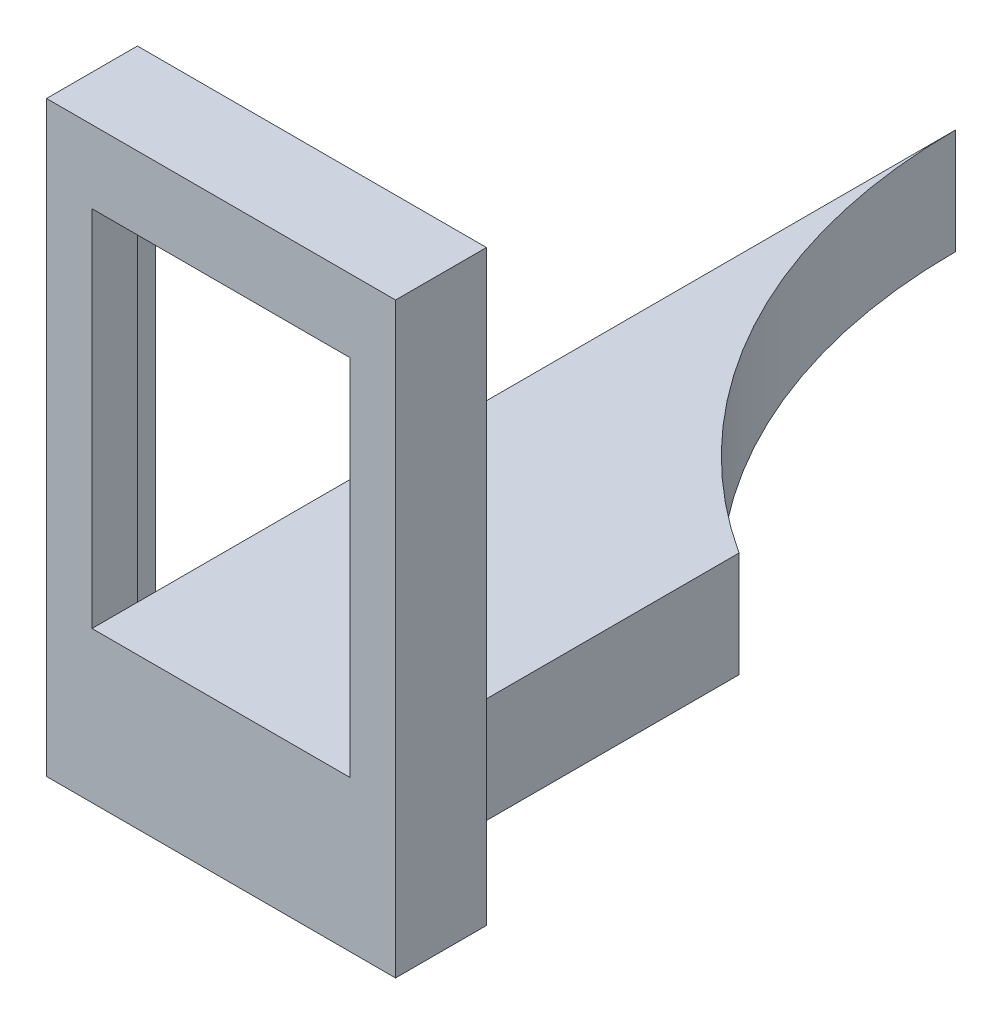
SolidWorks part; units mm, degrees
ref_plane "정면" through (0, 0, 0) normal (0, 0, 1) x (1, 0, 0)
ref_plane "윗면" through (0, 0, 0) normal (0, 1, 0) x (1, 0, 0)
ref_plane "우측면" through (0, 0, 0) normal (1, 0, 0) x (0, 0, -1)
sketch "스케치8" plane through (0, 0, 0) normal (0, 0, 1) x (1, 0, 0)
  line L0 (0, 60.6) -> (0, 0)
  line L1 (0, 0) -> (34.4, 0)
  line L2 (34.4, 0) -> (34.4, 60.6)
  line L3 (34.4, 60.6) -> (0, 60.6)
  line L4 (3, 54.6) -> (3, 3)
  line L5 (3, 3) -> (31.4, 3)
  line L6 (31.4, 3) -> (31.4, 54.6)
  line L7 (31.4, 54.6) -> (3, 54.6)
  point P8 (0, 0)
  point P9 (0, 0)
  dimension "D1" = 6
  dimension "D2" = 3
  dimension "D3" = 3
  dimension "D4" = 3
  dimension "D5" = 60.6
  dimension "D6" = 34.4
extrude "보스-돌출4" add sketch "스케치8" against normal blind 5
sketch "스케치9" plane through (0, 0, 0) normal (0, 0, 1) x (1, 0, 0)
  line L0 (31.4, 3) -> (31.4, 54.6) construction
  line L1 (3, 3) -> (31.4, 3)
  line L2 (3, 3) -> (3, 14.6)
  line L3 (3, 14.6) -> (31.4, 14.6)
  line L4 (31.4, 3) -> (31.4, 14.6)
  line L5 (31.4, 54.6) -> (3, 54.6) construction
  dimension "D1" = 40
extrude "보스-돌출5" add sketch "스케치9" against normal blind 95
sketch "스케치10" plane through (0, 14.6, 0) normal (0, 1, 0) x (1, 0, 0)
  circle A0 centre (65.2, 95) radius 62.2
  point P3 (0, 0)
  dimension "D1" = 124.4
extrude "컷-돌출3" cut sketch "스케치10" against normal blind 100
ref_plane "평면1" through (31.4, 14.6, -42.7851) normal (0, 0, 1) x (1, 0, 0)
sketch "스케치13" plane through (0, 0, 0) normal (0, 0, 1) x (1, 0, 0)
  line L0 (0, 60.6) -> (0, 0) construction
  line L1 (-2, -2) -> (36.4, -2)
  line L2 (-2, -2) -> (-2, 62.6)
  line L3 (-2, 62.6) -> (36.4, 62.6)
  line L4 (36.4, -2) -> (36.4, 62.6)
  line L5 (34.4, 0) -> (34.4, 60.6) construction
  line L6 (34.4, 60.6) -> (0, 60.6) construction
  line L7 (0, 0) -> (34.4, 0) construction
  line L8 (0, 0) -> (34.4, 0)
  line L9 (34.4, 0) -> (34.4, 60.6)
  line L10 (0, 60.6) -> (0, 0)
  line L11 (34.4, 60.6) -> (0, 60.6)
  dimension "D1" = 2
  dimension "D2" = 2
  dimension "D3" = 2
  dimension "D4" = 2
extrude "보스-돌출7" add sketch "스케치13" against normal blind 10
